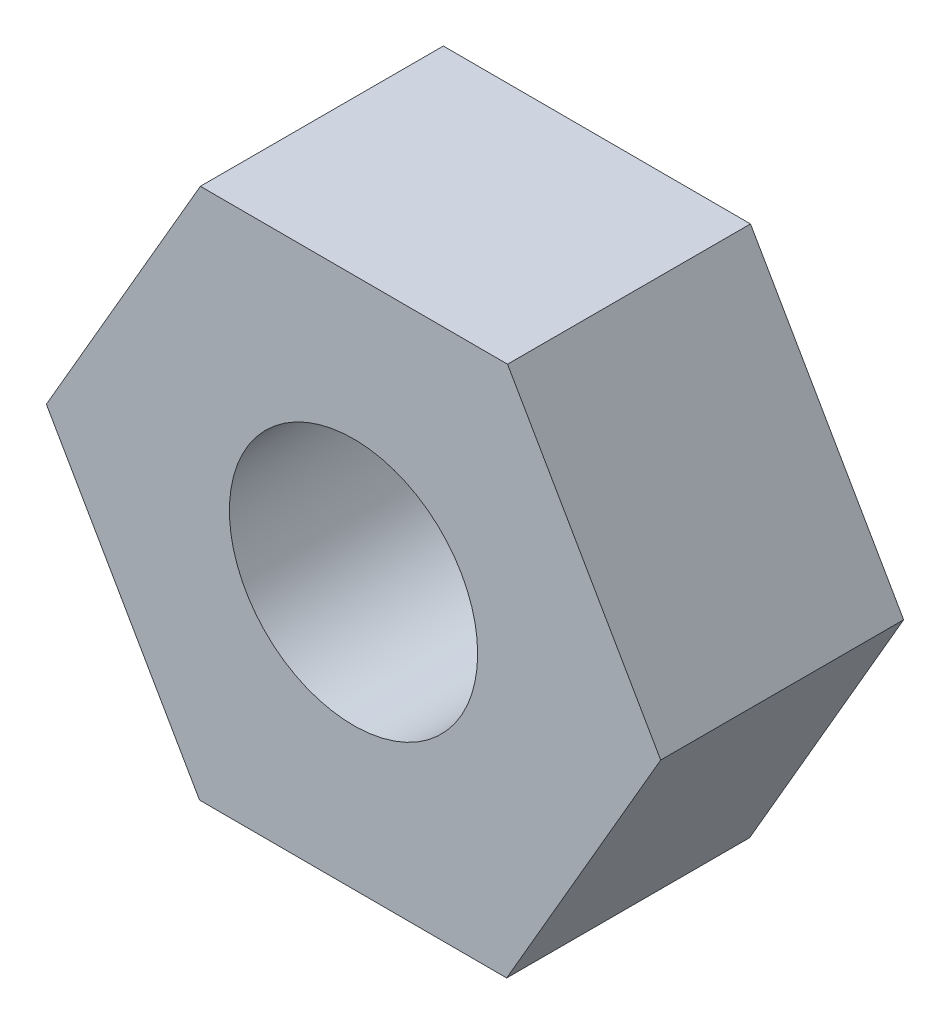
SolidWorks part; units mm, degrees
ref_plane "Front Plane" through (0, 0, 0) normal (0, 0, 1) x (1, 0, 0)
ref_plane "Top Plane" through (0, 0, 0) normal (0, 1, 0) x (1, 0, 0)
ref_plane "Right Plane" through (0, 0, 0) normal (1, 0, 0) x (0, 0, -1)
sketch "Sketch1" plane through (0, 0, 0) normal (0, 0, 1) x (1, 0, 0)
  line L1 (-2.1934, 3.8136) -> (-4.3994, 0.0072)
  line L2 (-4.3994, 0.0072) -> (-2.206, -3.8064)
  line L3 (-2.206, -3.8064) -> (2.1934, -3.8136)
  line L4 (2.1934, -3.8136) -> (4.3994, -0.0072)
  line L5 (4.3994, -0.0072) -> (2.206, 3.8064)
  line L6 (2.206, 3.8064) -> (-2.1934, 3.8136)
  circle A0 centre (0, 0) radius 3.81 construction
  dimension "D1" = 7.62
extrude "Boss-Extrude1" add sketch "Sketch1" along normal blind 3.4798
sketch "Sketch2" plane through (0, 0, 3.4798) normal (0, 0, 1) x (1, 0, 0)
  circle A0 centre (0, 0) radius 1.778
  dimension "D1" = 3.556
extrude "Cut-Extrude1" cut sketch "Sketch2" against normal blind 3.4798
